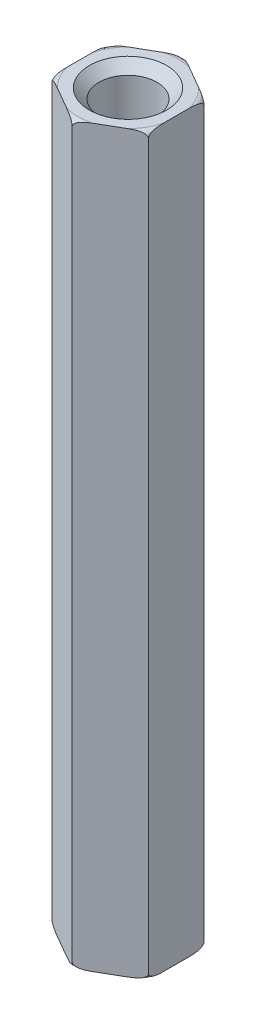
SolidWorks part; units mm, degrees
ref_plane "Front Plane" through (0, 0, 0) normal (0, 0, 1) x (1, 0, 0)
ref_plane "Top Plane" through (0, 0, 0) normal (0, 1, 0) x (1, 0, 0)
ref_plane "Right Plane" through (0, 0, 0) normal (1, 0, 0) x (0, 0, -1)
sketch "Sketch2" plane through (0, 0, 0) normal (0, 1, 0) x (1, 0, 0)
  line L1 (0, -2.8868) -> (2.5, -1.4434)
  line L2 (2.5, -1.4434) -> (2.5, 1.4434)
  line L3 (2.5, 1.4434) -> (0, 2.8868)
  line L4 (0, 2.8868) -> (-2.5, 1.4434)
  line L5 (-2.5, 1.4434) -> (-2.5, -1.4434)
  line L6 (-2.5, -1.4434) -> (0, -2.8868)
  circle A0 centre (0, 0) radius 2.5 construction
  circle A1 centre (0, 0) radius 1.5
  dimension "D1" = 3
  dimension "D2" = 5
extrude "Boss-Extrude2" add sketch "Sketch2" along normal mid plane 38 contours A1
chamfer "Chamfer1" distance 0.5 angle 45 2 edges at (0, -19, 1.5) (0, 19, 1.5)
sketch "Sketch4" plane through (0, 0, 0) normal (1, 0, 0) x (0, 0, -1)
  line L1 (-2.8868, 19) -> (-2.8868, -19) construction
  line L3 (-2.8868, 19) -> (-1.4434, 19) construction
  line L4 (-2.8868, 18.7) -> (-2.8868, 19)
  line L5 (-2.8868, 19) -> (-2.5868, 19)
  arc A0 (-2.8868, 18.7) -> (-2.5868, 19) centre (-2.5868, 18.7) cw
  dimension "D1" = 0.3
ref_axis "Axis1" through (0, 57.75, 0) along (0, -1, 0)
revolve "Cut-Revolve1" cut sketch "Sketch4" angle 360 about axis through (0, 57.75, 0) along (0, -1, 0)
mirror "Mirror1" about plane through (0, 0, 0) normal (0, 1, 0) of "Cut-Revolve1"
